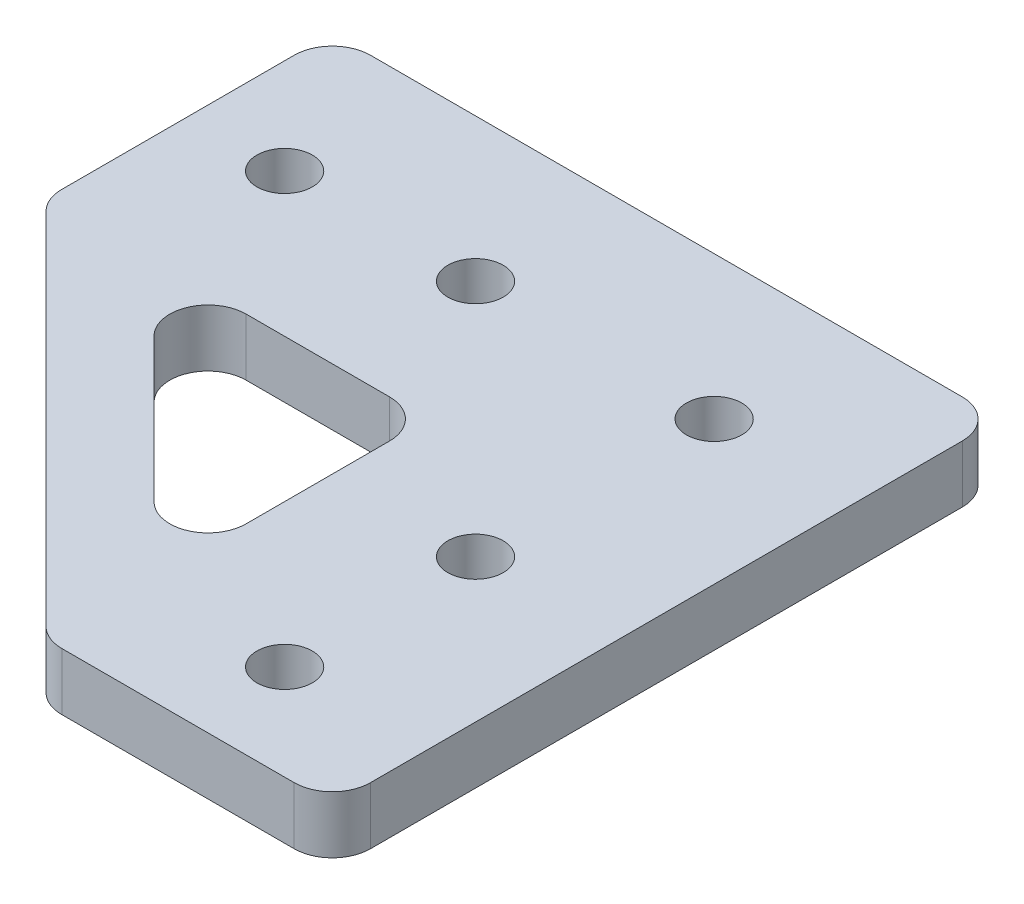
SolidWorks part; units mm, degrees
material "Thornel Mat VMA"
ref_plane "前视基准面" through (0, 0, 0) normal (0, 0, 1) x (1, 0, 0)
ref_plane "上视基准面" through (0, 0, 0) normal (0, 1, 0) x (1, 0, 0)
ref_plane "右视基准面" through (0, 0, 0) normal (1, 0, 0) x (0, 0, -1)
other "Configuration Table"
sketch "草图1" plane through (0, 0, 0) normal (0, 1, 0) x (1, 0, 0)
  line L0 (-35, -7.5) -> (0, -7.5) construction
  line L1 (0, 0) -> (-35, 0)
  line L2 (0, 0) -> (0, -35)
  line L3 (0, -35) -> (-15, -35)
  line L4 (-35, 0) -> (-35, -15)
  line L7 (-35, -15) -> (-15, -15)
  line L8 (-15, -35) -> (-15, -15)
  line L9 (-7.5, -35) -> (-7.5, 0) construction
  circle A0 centre (-7.5, -7.5) radius 1.45
  circle A1 centre (-20, -7.5) radius 1.45
  circle A2 centre (-30, -7.5) radius 1.45
  circle A3 centre (-7.5, -20) radius 1.45
  circle A4 centre (-7.5, -30) radius 1.45
  dimension "D3" = 2.9
  dimension "D4" = 2.9
  dimension "D5" = 2.9
  dimension "D6" = 5
  dimension "D7" = 10
  dimension "D9" = 2.9
  dimension "D10" = 2.9
  dimension "D12" = 10
  dimension "D1" = 15
  dimension "D2" = 15
  dimension "D8" = 35
  dimension "D11" = 5
  dimension "D13" = 35
extrude "凸台-拉伸1" add sketch "草图1" along normal blind 3
sketch "草图2" plane through (0, 3, 0) normal (0, 1, 0) x (1, 0, 0)
  line L0 (-35, -15) -> (-15, -35)
  line L1 (-15, -35) -> (-15, -29.3431)
  line L2 (-15, -15) -> (-15, -35) construction
  line L3 (-15, -29.3431) -> (-29.3431, -15)
  line L4 (-35, -15) -> (-15, -15) construction
  line L5 (-29.3431, -15) -> (-35, -15)
  dimension "D1" = 4
extrude "凸台-拉伸2" add sketch "草图2" against normal blind 3
fillet "圆角1" radius 2 8 edges at (-15, 1.5, 35) (-35, 1.5, 15) (-35, 1.5, 0) (0, 1.5, 0) (0, 1.5, 35) (-15, 1.5, 29.3431) (-29.3431, 1.5, 15) (-15, 1.5, 15)
